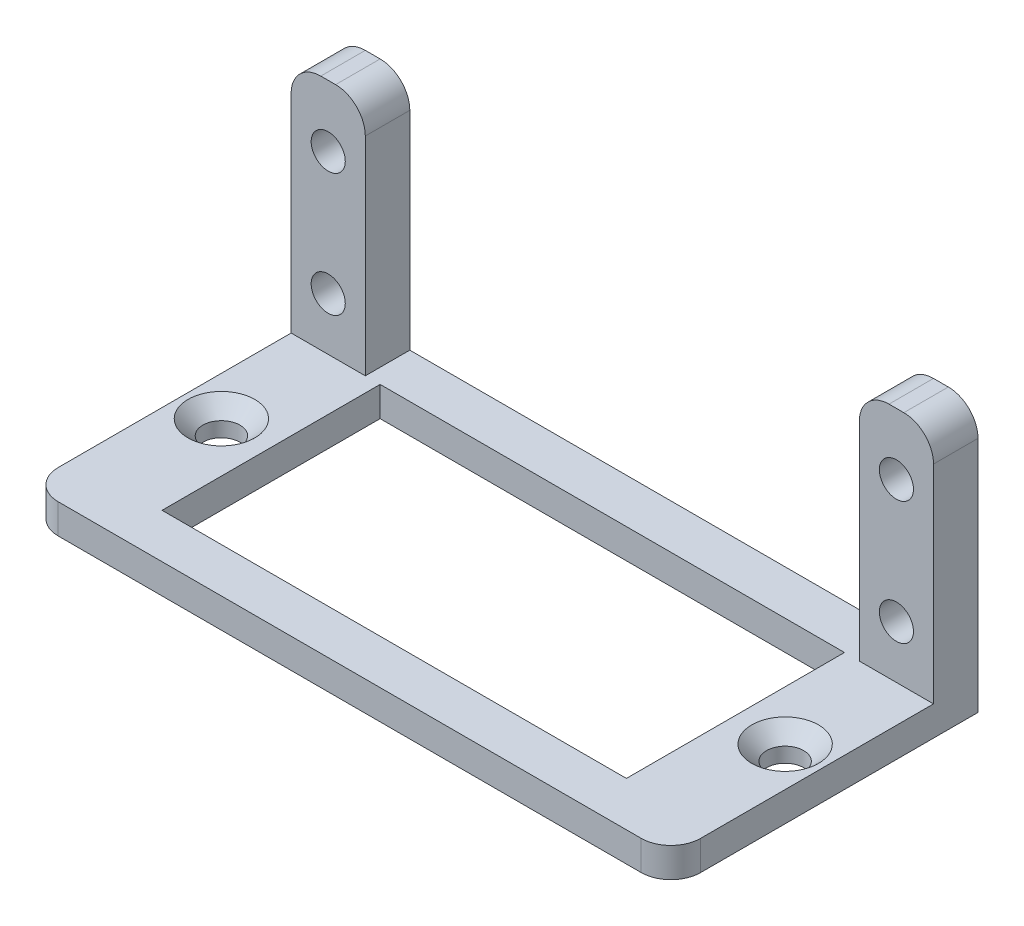
SolidWorks part; units mm, degrees
ref_plane "Front Plane" through (0, 0, 0) normal (0, 0, 1) x (1, 0, 0)
ref_plane "Top Plane" through (0, 0, 0) normal (0, 1, 0) x (1, 0, 0)
ref_plane "Right Plane" through (0, 0, 0) normal (1, 0, 0) x (0, 0, -1)
sketch "Sketch1" plane through (0, 0, 0) normal (0, 1, 0) x (1, 0, 0)
  line L1 (0, 0) -> (54.991, 0)
  line L2 (0, 0) -> (0, 26.289)
  line L3 (0, 26.289) -> (54.991, 26.289)
  line L4 (54.991, 0) -> (54.991, 26.289)
  line L5 (7.62, 22.479) -> (47.371, 22.479)
  line L6 (7.62, 22.479) -> (7.62, 3.81)
  line L7 (7.62, 3.81) -> (47.371, 3.81)
  line L8 (47.371, 22.479) -> (47.371, 3.81)
  circle A1 centre (51.6255, 13.1445) radius 1.5875
  circle A2 centre (3.3655, 13.1445) radius 1.5875
  point P14 (1.778, 13.1445)
  point P15 (53.213, 13.1445)
  point P16 (0, 0)
  point P17 (0, 13.1445)
  dimension "D9" = 3.175
  dimension "D1" = 54.991
  dimension "D2" = 26.289
  dimension "D3" = 7.62
  dimension "D4" = 7.62
  dimension "D5" = 3.81
  dimension "D6" = 3.81
  dimension "D7" = 1.778
  dimension "D8" = 1.778
extrude "Base" add sketch "Sketch1" along normal blind 2.54
sketch "Sketch2" plane through (0, 2.54, 0) normal (0, 1, 0) x (1, 0, 0)
  line L0 (54.991, 0) -> (54.991, 26.289) construction
  line L1 (0, 26.289) -> (54.991, 26.289)
  line L2 (0, 26.289) -> (0, 22.479)
  line L3 (0, 22.479) -> (54.991, 22.479)
  line L4 (54.991, 26.289) -> (54.991, 22.479)
  line L5 (47.371, 22.479) -> (7.62, 22.479) construction
extrude "4 hole" add sketch "Sketch2" along normal blind 20.32
sketch "Sketch3" plane through (0, 0, -22.479) normal (0, 0, 1) x (1, 0, 0)
  line L0 (0, 22.86) -> (54.991, 22.86) construction
  line L1 (6.35, 22.86) -> (48.641, 22.86)
  line L2 (6.35, 22.86) -> (6.35, 2.54)
  line L3 (6.35, 2.54) -> (48.641, 2.54)
  line L4 (48.641, 22.86) -> (48.641, 2.54)
  line L5 (47.371, 2.54) -> (54.991, 2.54) construction
  line L6 (0, 22.86) -> (0, 2.54) construction
  line L7 (54.991, 22.86) -> (54.991, 2.54) construction
  dimension "D1" = 6.35
  dimension "D2" = 6.35
extrude "gap" cut sketch "Sketch3" against normal through all
fillet "Fillet1" radius 2.54 6 edges at (54.991, 1.27, 0) (0, 1.27, 0) (54.991, 22.86, -24.384) (48.641, 22.86, -24.384) (6.35, 22.86, -24.384) (0, 22.86, -24.384)
chamfer "Chamfer1" distance 1.27 angle 45 2 edges at (3.3655, 2.54, -11.557) (51.6255, 2.54, -11.557)
sketch "Sketch4" plane through (0, 0, -22.479) normal (0, 0, 1) x (1, 0, 0)
  line L0 (2.54, 22.86) -> (3.81, 22.86) construction
  line L1 (51.181, 22.86) -> (52.451, 22.86) construction
  circle A0 centre (3.175, 17.5895) radius 1.4605
  circle A1 centre (3.175, 7.0485) radius 1.4605
  circle A2 centre (51.816, 17.5895) radius 1.4605
  circle A3 centre (51.816, 7.0485) radius 1.4605
  point P8 (3.175, 22.86)
  point P9 (51.816, 22.86)
  point P12 (3.175, 16.129)
  point P15 (3.175, 8.509)
  point P16 (3.175, 19.05)
  point P17 (3.175, 5.588)
  point P18 (51.816, 19.05)
  point P19 (51.816, 16.129)
  point P20 (51.816, 8.509)
  point P21 (51.816, 5.588)
  point P22 (0, 0)
  point P23 (0, 0)
  dimension "D1" = 2.921
  dimension "D2" = 3.81
  dimension "D3" = 7.62
extrude "servo screw holes" cut sketch "Sketch4" against normal through all
